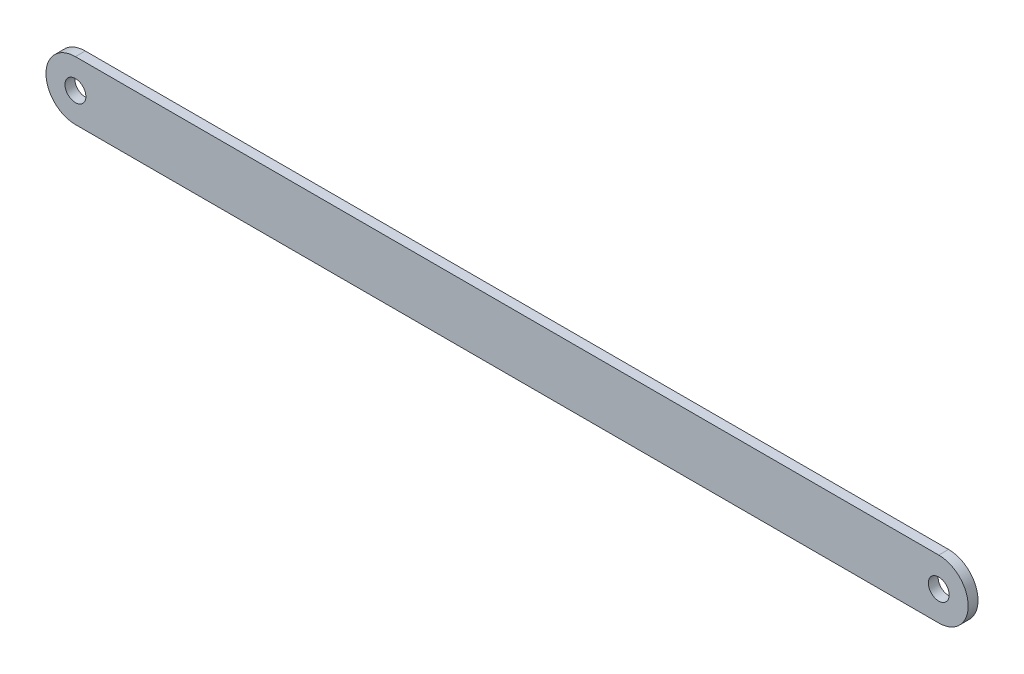
SolidWorks part; units mm, degrees
material "6063-O"
ref_plane "Front Plane" through (0, 0, 0) normal (0, 0, 1) x (1, 0, 0)
ref_plane "Top Plane" through (0, 0, 0) normal (0, 1, 0) x (1, 0, 0)
ref_plane "Right Plane" through (0, 0, 0) normal (1, 0, 0) x (0, 0, -1)
sketch "Sketch2" plane through (0, 0, 0) normal (0, 0, 1) x (1, 0, 0)
  line L0 (139.7, 0) -> (-139.7, 0) construction
  line L1 (1.7463, 0) -> (-1.7463, 0) construction
  line L2 (139.7, -9.525) -> (-139.7, -9.525)
  line L3 (139.7, 9.525) -> (-139.7, 9.525)
  arc A0 (139.7, -9.525) -> (139.7, 9.525) centre (139.7, 0) ccw
  arc A1 (-139.7, 9.525) -> (-139.7, -9.525) centre (-139.7, 0) ccw
  point P5 (0, 0)
  dimension "D1" = 19.05
  dimension "D2" = 298.45
extrude "Boss-Extrude1" add sketch "Sketch2" along normal mid plane 3.175
hole_wizard "1/4 Clearance Hole1" positions "Sketch4" profile "Sketch5" hole size "1/4" standard "ANSI Inch" end condition through all
sketch "Sketch4" plane through (0, 0, 1.5875) normal (0, 0, 1) x (1, 0, 0)
  point P0 (-139.7, 0)
  point P3 (139.7, 0)
sketch "Sketch5" plane through (-139.7, 0, 1.5875) normal (1, 0, 0) x (0, -1, 0)
  line L0 (0, 0) -> (0, 3.175)
  line L1 (0, 3.175) -> (3.3782, 3.175)
  line L2 (3.3782, 3.175) -> (3.3782, 0)
  line L5 (3.3782, 0) -> (0, 0)
  line L11 (0, -6.35) -> (0, 107.95) construction
  dimension "Thru Hole Dia." = 6.7564
  dimension "Thru Hole Depth" = 3.175
